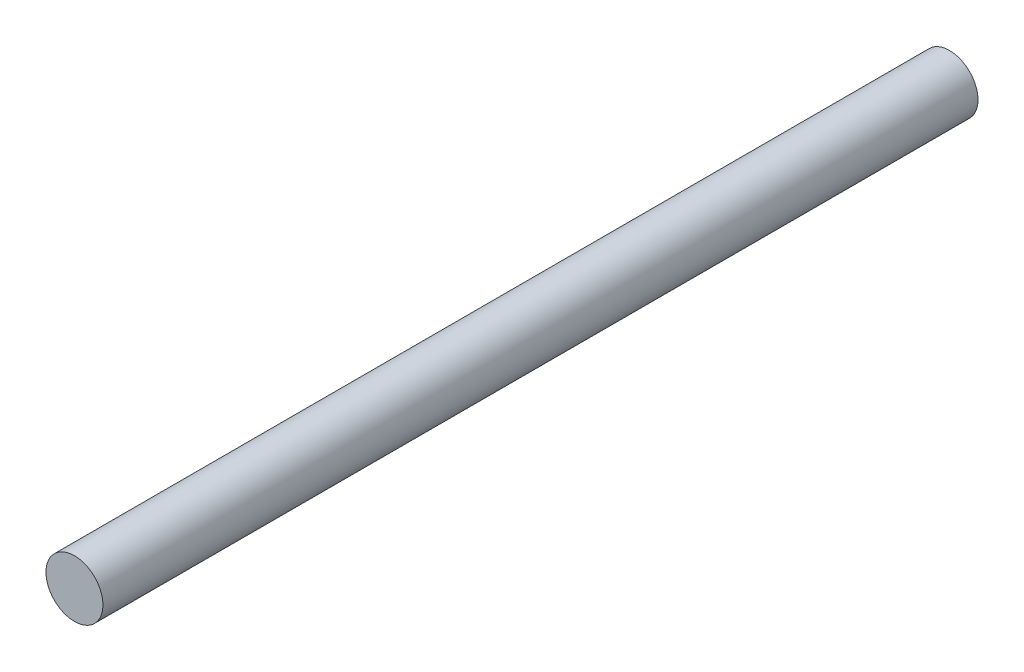
SolidWorks part; units mm, degrees
ref_plane "Front Plane" through (0, 0, 0) normal (0, 0, 1) x (1, 0, 0)
ref_plane "Top Plane" through (0, 0, 0) normal (0, 1, 0) x (1, 0, 0)
ref_plane "Right Plane" through (0, 0, 0) normal (1, 0, 0) x (0, 0, -1)
sketch "Sketch1" plane through (0, 0, 0) normal (0, 0, 1) x (1, 0, 0)
  circle A0 centre (0, 0) radius 7
  dimension "D1" = 14
extrude "Boss-Extrude1" add sketch "Sketch1" along normal blind 215
